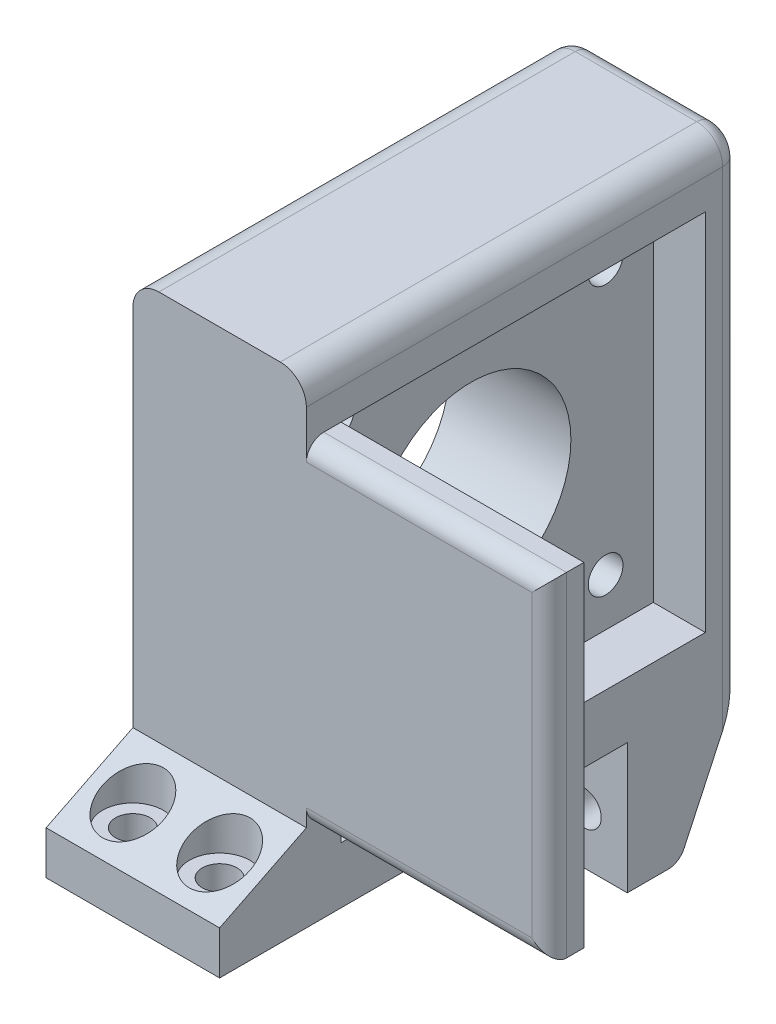
SolidWorks part; units mm, degrees
ref_plane "Front Plane" through (0, 0, 0) normal (0, 0, 1) x (1, 0, 0)
ref_plane "Top Plane" through (0, 0, 0) normal (0, 1, 0) x (1, 0, 0)
ref_plane "Right Plane" through (0, 0, 0) normal (1, 0, 0) x (0, 0, -1)
sketch "Sketch1" plane through (0, 0, 0) normal (0, 1, 0) x (1, 0, 0)
  line L1 (0, 0) -> (-20, 0)
  line L2 (0, 0) -> (0, -50)
  line L3 (0, -50) -> (-20, -50)
  line L4 (-20, 0) -> (-20, -50)
  dimension "D1" = 20
  dimension "D2" = 50
extrude "Boss-Extrude1" add sketch "Sketch1" along normal blind 70
sketch "Sketch2" plane through (0, 0, 0) normal (1, 0, 0) x (0, 0, -1)
  line L0 (-50, 70) -> (0, 70) construction
  line L1 (0, 70) -> (0, 0) construction
  line L2 (0, 42.5) -> (-50, 42.5) construction
  line L3 (-25, 70) -> (-25, 0) construction
  line L4 (-25, 70) -> (-25, 0) construction
  line L7 (-50, 70) -> (-50, 0) construction
  circle A0 centre (-9.5, 58) radius 2
  circle A4 centre (-25, 42.5) radius 11.5
  circle A5 centre (-9.5, 27) radius 2
  circle A8 centre (-40.5, 27) radius 2
  circle A9 centre (-40.5, 58) radius 2
  dimension "D1" = 4
  dimension "D2" = 12
  dimension "D3" = 15.5
  dimension "D6" = 23
  dimension "D7" = 0
  dimension "D8" = 0
  dimension "D4" = 15.5
  dimension "D5" = 0
extrude "Cut-Extrude2" cut sketch "Sketch2" against normal blind 60
sketch "Sketch4" plane through (0, 0, 0) normal (1, 0, 0) x (0, 0, -1)
  line L1 (-50, 0) -> (-13, 0)
  line L2 (-50, 0) -> (-50, 15)
  line L3 (-50, 15) -> (-13, 15)
  line L4 (-13, 0) -> (-13, 15)
  circle A0 centre (-25, 42.5) radius 11.5 construction
  dimension "D1" = 15
  dimension "D2" = 12
extrude "Cut-Extrude3" cut sketch "Sketch4" against normal blind 60
sketch "Sketch8" plane through (0, 0, 0) normal (0, 0, -1) x (-1, 0, 0)
  line L0 (0, 0) -> (20, 0) construction
  line L1 (20, 70) -> (20, 0) construction
  line L2 (0, 70) -> (0, 0) construction
  circle A0 centre (15, 6) radius 2
  circle A1 centre (5, 6) radius 2
  dimension "D1" = 4
  dimension "D2" = 6
  dimension "D3" = 5
  dimension "D4" = 4
  dimension "D5" = 0
  dimension "D6" = 5
extrude "Cut-Extrude5" cut sketch "Sketch8" against normal blind 15
sketch "Sketch9" plane through (0, 0, 0) normal (1, 0, 0) x (0, 0, -1)
  line L0 (0, 42.5) -> (-50, 42.5) construction
  line L1 (-4, 63.5) -> (-46, 63.5)
  line L2 (-4, 63.5) -> (-4, 21.5)
  line L3 (-4, 21.5) -> (-46, 21.5)
  line L4 (-46, 63.5) -> (-46, 21.5)
  line L5 (0, 70) -> (0, 0) construction
  line L6 (-50, 70) -> (-50, 15) construction
  line L7 (-25, 70) -> (-25, 15) construction
  line L8 (-50, 70) -> (0, 70) construction
  line L9 (-13, 15) -> (-50, 15) construction
  circle A0 centre (-25, 42.5) radius 11.5 construction
  dimension "D1" = 0
  dimension "D2" = 42
  dimension "D3" = 21
  dimension "D4" = 42
  dimension "D5" = 21
  dimension "D6" = 0
extrude "Cut-Extrude6" cut sketch "Sketch9" against normal blind 6
sketch "Sketch11" plane through (0, 0, 0) normal (1, 0, 0) x (0, 0, -1)
  line L7 (-7, 0) -> (0, 0)
  line L8 (-13, 0) -> (0, 0) construction
  line L9 (0, 0) -> (0, 15)
  line L10 (0, 70) -> (0, 0) construction
  line L11 (0, 15) -> (-7, 0)
  line L12 (-13, 15) -> (-50, 15) construction
  dimension "D1" = 0
  dimension "D2" = 6
extrude "Cut-Extrude8" cut sketch "Sketch11" against normal blind 30
sketch "Sketch12" plane through (0, 0, 50) normal (0, 0, 1) x (1, 0, 0)
  line L0 (-20, 70) -> (-20, 15) construction
  line L1 (0, 15) -> (-20, 15)
  line L2 (0, 15) -> (0, 20)
  line L3 (0, 20) -> (-20, 20)
  line L4 (-20, 15) -> (-20, 20)
  dimension "D1" = 5
extrude "Boss-Extrude2" add sketch "Sketch12" along normal blind 10
sketch "Sketch14" plane through (0, 0, 0) normal (1, 0, 0) x (0, 0, -1)
  line L0 (-50, 20) -> (-60, 20)
  line L1 (-60, 20) -> (-50, 20) construction
  line L2 (-60, 20) -> (-50, 25)
  line L3 (-50, 70) -> (-50, 20) construction
  line L4 (-50, 25) -> (-50, 20)
  dimension "D1" = 5
extrude "Boss-Extrude3" add sketch "Sketch14" against normal up to vertex (20 mm away)
sketch "Sketch15" plane through (0, 15, 0) normal (0, -1, 0) x (-1, 0, 0)
  line L0 (0, -13) -> (0, -60) construction
  line L1 (20, -13) -> (20, -60) construction
  line L2 (20, -60) -> (0, -60) construction
  circle A0 centre (5, -55) radius 2
  circle A1 centre (15, -55) radius 2
  dimension "D1" = 4
  dimension "D2" = 4
  dimension "D3" = 5
  dimension "D4" = 5
  dimension "D5" = 5
  dimension "D6" = 5
extrude "Cut-Extrude9" cut sketch "Sketch15" against normal blind 10
sketch "Sketch17" plane through (0, 0, 0) normal (0, 0, -1) x (-1, 0, 0)
  circle A0 centre (15, 6) radius 3.5
  circle A1 centre (5, 6) radius 3.5
  dimension "D1" = 7
  dimension "D2" = 7
extrude "Cut-Extrude11" cut sketch "Sketch17" against normal blind 8
sketch "Sketch18" plane through (0, 70, 0) normal (0, 1, 0) x (1, 0, 0)
  circle A0 centre (-15, -55) radius 3.5
  circle A1 centre (-5, -55) radius 3.5
  dimension "D1" = 7
  dimension "D2" = 7
extrude "Cut-Extrude12" cut sketch "Sketch18" against normal blind 50
fillet "Fillet2" radius 3 1 edges at (0, 70, 25)
fillet "Fillet3" radius 3 1 edges at (-20, 70, 25)
fillet "Fillet5" radius 2 5 edges at (0, 41, 0) (-0.8787, 69.1213, 0) (-20, 41, 0) (-19.1213, 69.1213, 0) (-10, 70, 0)
fillet "Fillet6" radius 2 1 edges at (-10, 0, 7)
sketch "Sketch19" plane through (0, 0, 0) normal (1, 0, 0) x (0, 0, -1)
  line L1 (-46, 63.5) -> (-50, 63.5)
  line L2 (-46, 63.5) -> (-46, 25)
  line L3 (-46, 25) -> (-50, 25)
  line L4 (-50, 63.5) -> (-50, 25)
extrude "Boss-Extrude4" add sketch "Sketch19" along normal blind 28
fillet "Fillet7" radius 2 3 edges at (14, 25, 50) (14, 63.5, 50) (28, 44.25, 50)
